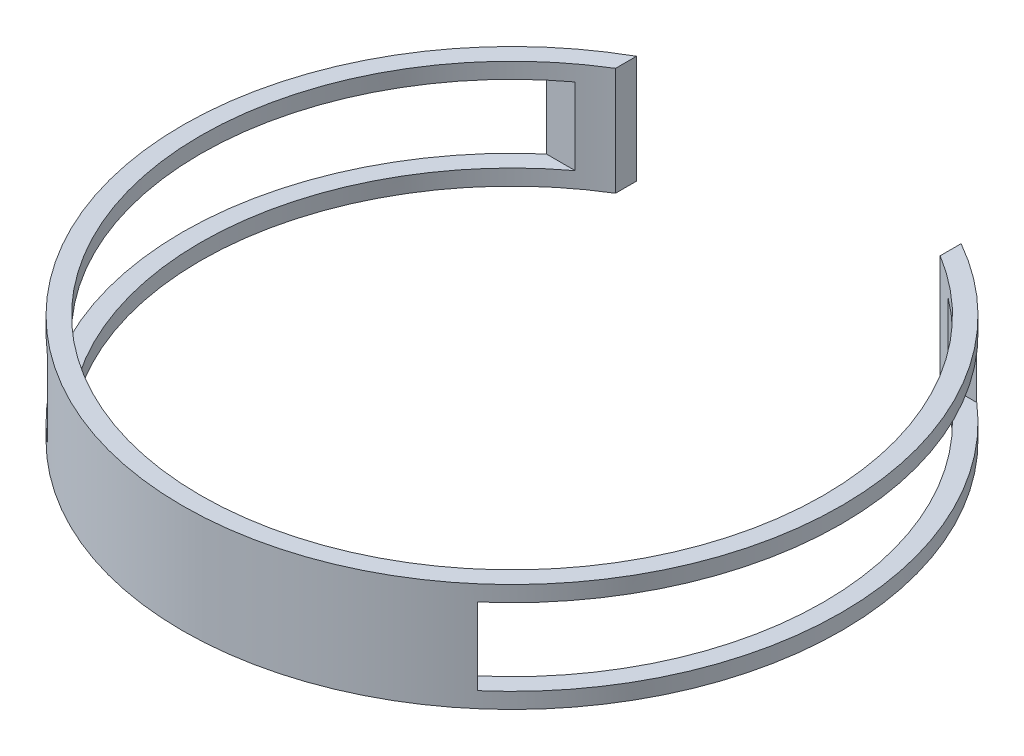
SolidWorks part; units mm, degrees
ref_plane "Front Plane" through (0, 0, 0) normal (0, 0, 1) x (1, 0, 0)
ref_plane "Top Plane" through (0, 0, 0) normal (0, 1, 0) x (1, 0, 0)
ref_plane "Right Plane" through (0, 0, 0) normal (1, 0, 0) x (0, 0, -1)
sketch "Sketch2" plane through (0, 0, 0) normal (0, 1, 0) x (1, 0, 0)
  circle A0 centre (0, 0) radius 91.355
  circle A1 centre (0, 0) radius 86.355
extrude "Boss-Extrude1" add sketch "Sketch2" along normal mid plane 30
sketch "Sketch5" plane through (0, 0, 0) normal (0, 0, 1) x (1, 0, 0)
  line L0 (86.355, 15) -> (-86.355, 15) construction
  line L1 (-45, -15) -> (45, -15)
  line L2 (-45, -15) -> (-45, 15)
  line L3 (-45, 15) -> (45, 15)
  line L4 (45, -15) -> (45, 15)
  line L5 (-45, -15) -> (45, 15) construction
  line L6 (-45, 15) -> (45, -15) construction
  point P0 (0, 0)
extrude "Cut-Extrude1" cut sketch "Sketch5" against normal through all
sketch "Sketch6" plane through (0, 0, 0) normal (1, 0, 0) x (0, 0, -1)
  line L1 (69.186, -10.644) -> (-69.186, -10.644)
  line L2 (69.186, -10.644) -> (69.186, 10.644)
  line L3 (69.186, 10.644) -> (-69.186, 10.644)
  line L4 (-69.186, -10.644) -> (-69.186, 10.644)
  line L5 (69.186, -10.644) -> (-69.186, 10.644) construction
  line L6 (69.186, 10.644) -> (-69.186, -10.644) construction
  point P0 (0, 0)
extrude "Cut-Extrude2" cut sketch "Sketch6" against normal through all both and the other way through all
